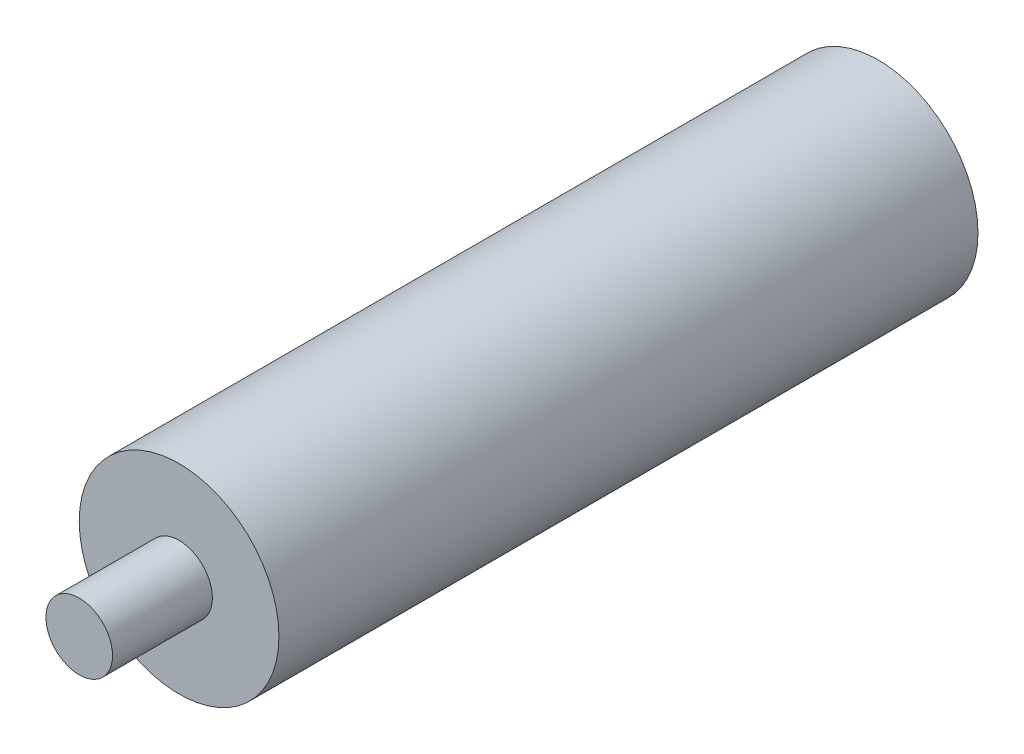
SolidWorks part; units mm, degrees
ref_plane "정면" through (0, 0, 0) normal (0, 0, 1) x (1, 0, 0)
ref_plane "윗면" through (0, 0, 0) normal (0, 1, 0) x (1, 0, 0)
ref_plane "우측면" through (0, 0, 0) normal (1, 0, 0) x (0, 0, -1)
sketch "스케치1" plane through (0, 0, 0) normal (0, 0, 1) x (1, 0, 0)
  circle A0 centre (0, 0) radius 3
  dimension "D1" = 6
extrude "보스-돌출1" add sketch "스케치1" along normal blind 21
sketch "스케치2" plane through (0, 0, 21) normal (0, 0, 1) x (1, 0, 0)
  circle A0 centre (0, 0) radius 1
  dimension "D1" = 2
extrude "보스-돌출2" add sketch "스케치2" along normal blind 3
